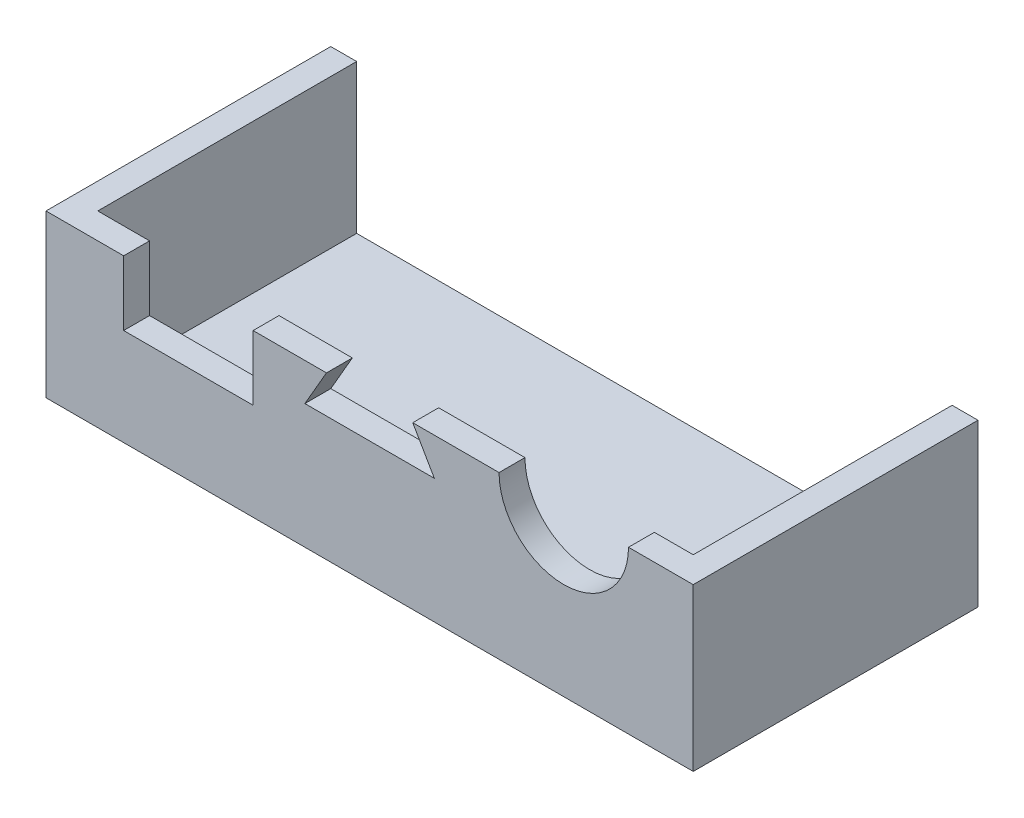
SolidWorks part; units mm, degrees
ref_plane "Front Plane" through (0, 0, 0) normal (0, 0, 1) x (1, 0, 0)
ref_plane "Top Plane" through (0, 0, 0) normal (0, 1, 0) x (1, 0, 0)
ref_plane "Right Plane" through (0, 0, 0) normal (1, 0, 0) x (0, 0, -1)
sketch "Sketch1" plane through (0, 0, 0) normal (0, 0, 1) x (1, 0, 0)
  line L1 (125, -62.5) -> (-125, -62.5)
  line L2 (125, -62.5) -> (125, 62.5)
  line L3 (125, 62.5) -> (-125, 62.5)
  line L4 (-125, -62.5) -> (-125, 62.5)
  line L5 (125, -62.5) -> (-125, 62.5) construction
  line L6 (125, 62.5) -> (-125, -62.5) construction
  line L7 (115, -57.5) -> (-115, -57.5)
  line L8 (115, -57.5) -> (115, 57.5)
  line L9 (115, 57.5) -> (-115, 57.5)
  line L10 (-115, -57.5) -> (-115, 57.5)
  line L11 (115, -57.5) -> (-115, 57.5) construction
  line L12 (115, 57.5) -> (-115, -57.5) construction
  point P0 (0, 0)
  point P6 (0, 0)
  dimension "D1" = 250
  dimension "D2" = 125
  dimension "D3" = 230
extrude "Boss-Extrude1" add sketch "Sketch1" along normal blind 100
sketch "Sketch2" plane through (0, 0, 0) normal (0, 0, -1) x (-1, 0, 0)
  line L1 (125, 62.5) -> (-125, 62.5)
  line L2 (125, 62.5) -> (125, -62.5)
  line L3 (125, -62.5) -> (-125, -62.5)
  line L4 (-125, 62.5) -> (-125, -62.5)
sketch "Sketch3" plane through (0, 0, 100) normal (0, 0, 1) x (1, 0, 0)
  line L0 (-125, 0) -> (125, 0) construction
  line L1 (-125, 62.5) -> (125, 62.5)
  line L2 (-125, 62.5) -> (-125, -62.5)
  line L3 (-125, -62.5) -> (125, -62.5)
  line L4 (125, 62.5) -> (125, -62.5)
  line L5 (0, 62.5) -> (0, -62.5) construction
  line L6 (-25, -14.4338) -> (0, 28.8675)
  line L7 (-95, 25) -> (-45, 25)
  line L8 (-95, 25) -> (-95, -25)
  line L9 (-95, -25) -> (-45, -25)
  line L10 (-45, 25) -> (-45, -25)
  line L11 (-95, 25) -> (-45, -25) construction
  line L12 (-95, -25) -> (-45, 25) construction
  line L14 (-1.3522, 0) -> (0, -1.3522)
  line L18 (0, 28.8675) -> (25, -14.4338)
  line L19 (25, -14.4338) -> (-25, -14.4338)
  line L20 (-25, -14.4338) -> (12.5, 7.2169) construction
  line L21 (25, -14.4338) -> (-12.5, 7.2169) construction
  line L22 (0, 28.8675) -> (0, 0) construction
  circle A0 centre (75, 0) radius 25
  point P10 (-70, 0)
  point P20 (0, 0)
  point P27 (7.7505, -5.3087)
  point P28 (0, 0)
  line M21 (-125, 62.5) -> (-125, -62.5)
  line M22 (-125, -62.5) -> (125, -62.5)
  line M23 (125, -62.5) -> (125, 62.5)
  line M24 (125, 62.5) -> (-125, 62.5)
  line M25 (115, -57.5) -> (-115, -57.5)
  line M26 (-115, -57.5) -> (-115, 57.5)
  line M27 (-115, 57.5) -> (115, 57.5)
  line M28 (115, 57.5) -> (115, -57.5)
  dimension "D2" = 50
  dimension "D3" = 50
  dimension "D1" = 30
  dimension "D4" = 50
  dimension "D5" = 50
  dimension "D6" = 50
  dimension "D7" = 50
  dimension "D8" = 50
extrude "Boss-Extrude4" add sketch "Sketch3" along normal blind 10 contours A0 L7 L10 L9 L8 L18 L19 L6 M25 M28 M27 M26 | M24 M21 M22 M23 M28 M25 M26 M27
sketch "Sketch4" plane through (0, 0, 0) normal (0, 0, 1) x (1, 0, 0)
  line L0 (-138.2338, 0) -> (148.7616, 0)
extrude "Cut-Extrude1" cut sketch "Sketch4" against normal through all and the other way through all contours L0
